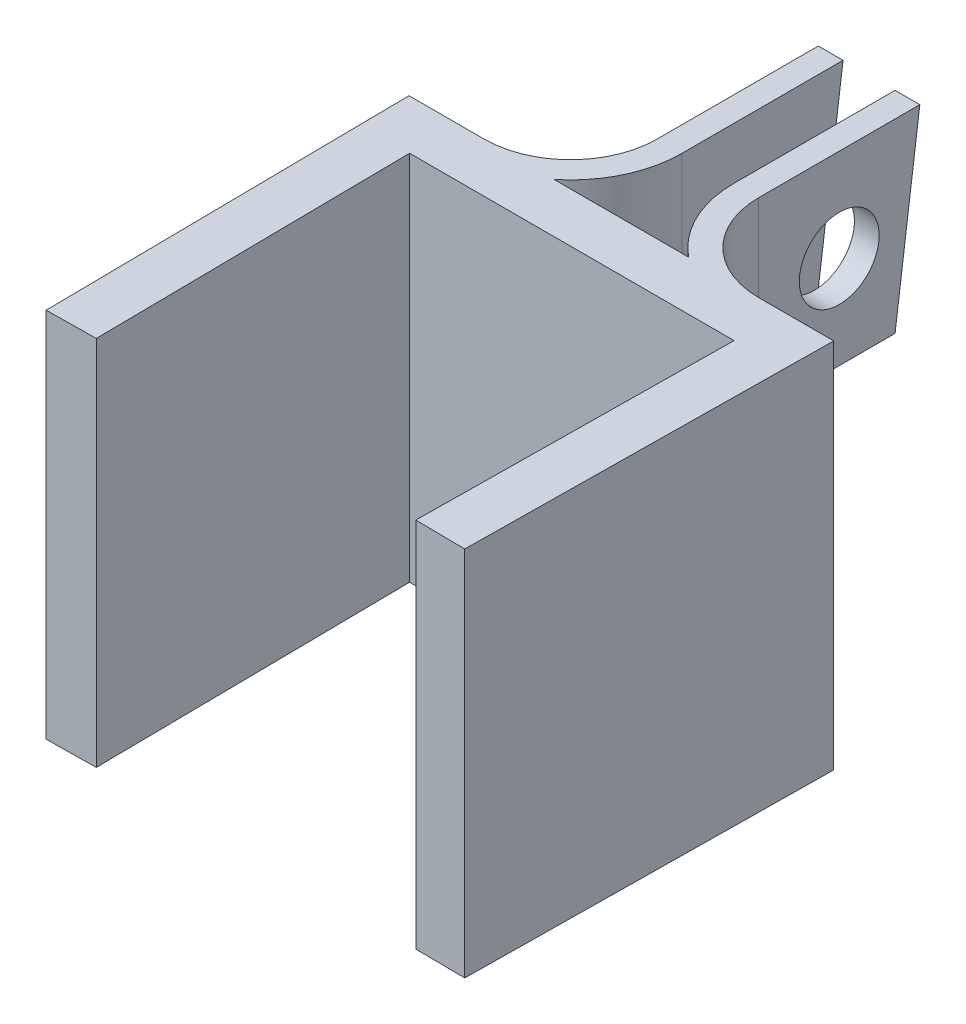
SolidWorks part; units mm, degrees
ref_plane "Front Plane" through (0, 0, 0) normal (0, 0, 1) x (1, 0, 0)
ref_plane "Top Plane" through (0, 0, 0) normal (0, 1, 0) x (1, 0, 0)
ref_plane "Right Plane" through (0, 0, 0) normal (1, 0, 0) x (0, 0, -1)
sketch "Sketch1" plane through (0, 0, 0) normal (0, 1, 0) x (1, 0, 0)
  line L0 (-12.8, -12.8) -> (-13.1, 12.8)
  line L1 (-12.8, 12.8) -> (12.8, 12.8) construction
  line L2 (-12.8, 12.8) -> (-12.8, -12.8) construction
  line L4 (12.8, 12.8) -> (12.8, -12.6) construction
  line L5 (-13.1, 12.8) -> (13.1, 12.8)
  line L6 (13.1, 12.8) -> (12.8, -12.6)
  line L7 (-16.7997, -12.8469) -> (-17.1471, 16.8)
  line L8 (-17.1471, 16.8) -> (17.1475, 16.8)
  line L9 (17.1475, 16.8) -> (16.7997, -12.6472)
  line L11 (-16.7997, -12.8469) -> (-12.8, -12.8)
  line L12 (12.8, -12.6) -> (16.7997, -12.6472)
  dimension "D1" = 25.6
  dimension "D2" = 25.4
  dimension "D3" = 0.3
  dimension "D4" = 0.3
  dimension "D5" = 4
extrude "Boss-Extrude1" add sketch "Sketch1" along normal blind 30
sketch "Sketch2" plane through (0, 30, 0) normal (0, 1, 0) x (1, 0, 0)
  line L0 (0.0002, 16.8) -> (0.0002, 30.8112) construction
  line L1 (17.1475, 16.8) -> (-17.1471, 16.8) construction
  line L2 (0.0002, 36.8) -> (-4.0998, 36.8) construction
  line L3 (0.0002, 36.8) -> (2.1002, 36.8) construction
  line L4 (-4.0998, 36.8) -> (-4.0998, 23.7851)
  line L5 (-2.0998, 36.8) -> (-2.0998, 23.7851)
  line L6 (-11.0849, 16.8) -> (-5.4334, 16.8)
  line L7 (-4.0998, 36.8) -> (-2.0998, 36.8)
  line L8 (4.1002, 36.8) -> (2.1002, 36.8)
  line L9 (11.0853, 16.8) -> (5.4337, 16.8)
  line L10 (2.1002, 36.8) -> (2.1002, 23.7851)
  line L11 (4.1002, 36.8) -> (4.1002, 23.7851)
  arc A0 (-4.0998, 23.7851) -> (-11.0849, 16.8) centre (-11.0849, 23.7851) cw
  arc A1 (-2.0998, 23.7851) -> (-5.4334, 16.8) centre (-11.0849, 23.7851) cw
  arc A2 (-2.0998, 23.7851) -> (-11.0849, 14.8) centre (-11.0849, 23.7851) cw construction
  arc A3 (4.1002, 23.7851) -> (11.0853, 16.8) centre (11.0853, 23.7851) ccw
  arc A4 (2.1002, 23.7851) -> (5.4337, 16.8) centre (11.0853, 23.7851) ccw
  dimension "D1" = 20
  dimension "D2" = 4.1
  dimension "D3" = 2
extrude "Boss-Extrude2" add sketch "Sketch2" against normal blind 15
sketch "Sketch3" plane through (-4.0998, 0, 0) normal (-1, 0, 0) x (0, 0, 1)
  line L0 (-36.8, 30) -> (-23.7851, 15) construction
  circle A0 centre (-30.2926, 22.5) radius 3.225
  dimension "D1" = 6.45
extrude "Cut-Extrude1" cut sketch "Sketch3" against normal blind 15
sketch "Sketch4" plane through (-4.0998, 0, 0) normal (-1, 0, 0) x (0, 0, 1)
  line L0 (-36.8, 30) -> (-38.8, 30)
  line L1 (-38.8, 30) -> (-36.8, 15)
  line L2 (-36.8, 15) -> (-36.8, 30)
sketch "Sketch6" plane through (4.1002, 0, 0) normal (1, 0, 0) x (0, 0, -1)
  line L4 (36.8, 30) -> (23.7851, 30)
  line L5 (23.7851, 30) -> (23.7851, 15)
  line L6 (23.7851, 15) -> (36.8, 15)
  line L7 (36.8, 15) -> (36.8, 30)
  line L8 (36.8, 30) -> (23.7851, 30)
  line L9 (23.7851, 30) -> (23.7851, 15)
  line L10 (23.7851, 15) -> (36.8, 15)
  line L12 (36.8, 15) -> (36.8, 30)
  circle A0 centre (30.2926, 22.5) radius 3.225 construction
  circle A1 centre (30.2926, 22.5) radius 3.225
  dimension "D1" = 0
sketch "Sketch8" plane through (4.1002, 0, 0) normal (1, 0, 0) x (0, 0, -1)
  line L0 (36.8, 30) -> (36.8, 15)
  line L1 (36.8, 15) -> (34.8, 15)
  line L2 (34.8, 15) -> (36.8, 30)
  dimension "D1" = 2
extrude "Cut-Extrude3" cut sketch "Sketch8" against normal blind 15
